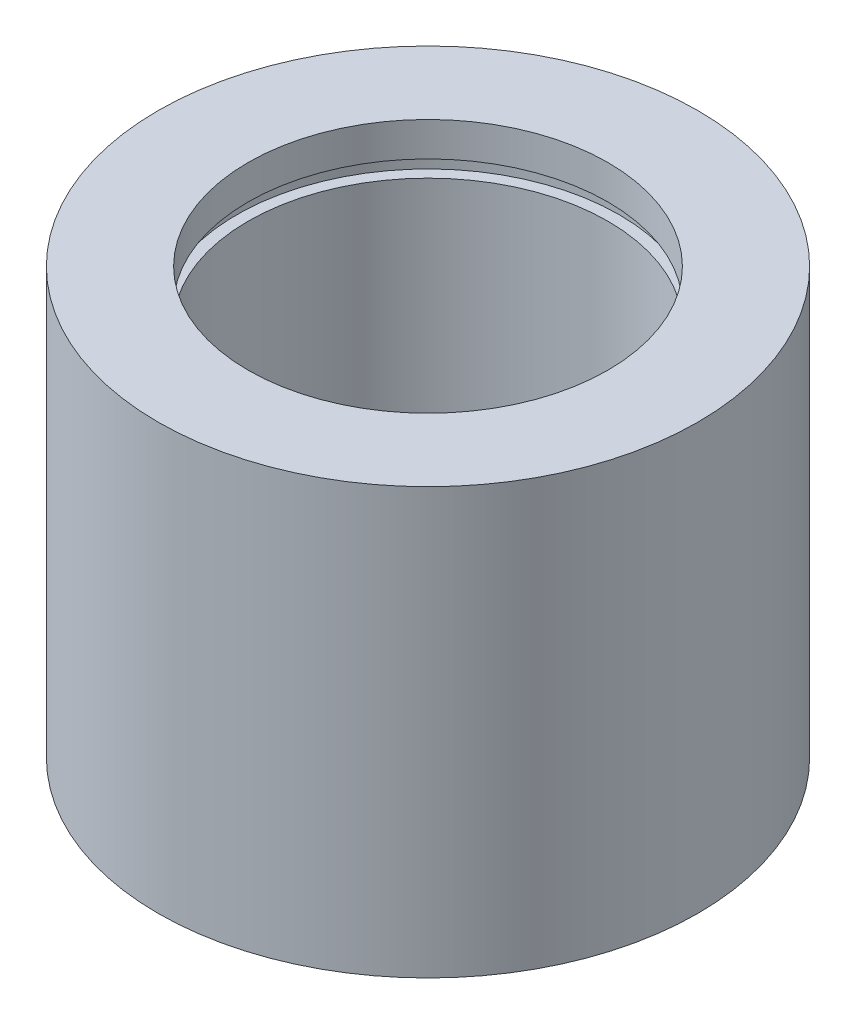
SolidWorks part; units mm, degrees
ref_plane "Front Plane" through (0, 0, 0) normal (0, 0, 1) x (1, 0, 0)
ref_plane "Top Plane" through (0, 0, 0) normal (0, 1, 0) x (1, 0, 0)
ref_plane "Right Plane" through (0, 0, 0) normal (1, 0, 0) x (0, 0, -1)
sketch "Sketch1" plane through (0, 0, 0) normal (0, 0, 1) x (1, 0, 0)
  line L0 (0, 0) -> (0, 59.5679) construction
  line L1 (20, 0) -> (30, 0)
  line L2 (30, 0) -> (30, 47.3)
  line L3 (30, 47.3) -> (20, 47.3)
  line L4 (20, 47.3) -> (20, 43.5)
  line L5 (20, 43.5) -> (21.25, 43.5)
  line L6 (21.25, 43.5) -> (21.25, 41.65)
  line L7 (21.25, 41.65) -> (20, 41.65)
  line L8 (20, 41.65) -> (20, 5.65)
  line L9 (20, 5.65) -> (21.25, 5.65)
  line L10 (21.25, 5.65) -> (21.25, 3.8)
  line L11 (21.25, 3.8) -> (20, 3.8)
  line L12 (20, 3.8) -> (20, 0)
  point P8 (23.0488, 3)
  dimension "D1" = 40
  dimension "D2" = 36
  dimension "D3" = 3.8
  dimension "D4" = 60
  dimension "D5" = 42.5
  dimension "D6" = 1.85
revolve "Revolve1" add sketch "Sketch1" angle 360 about L0
